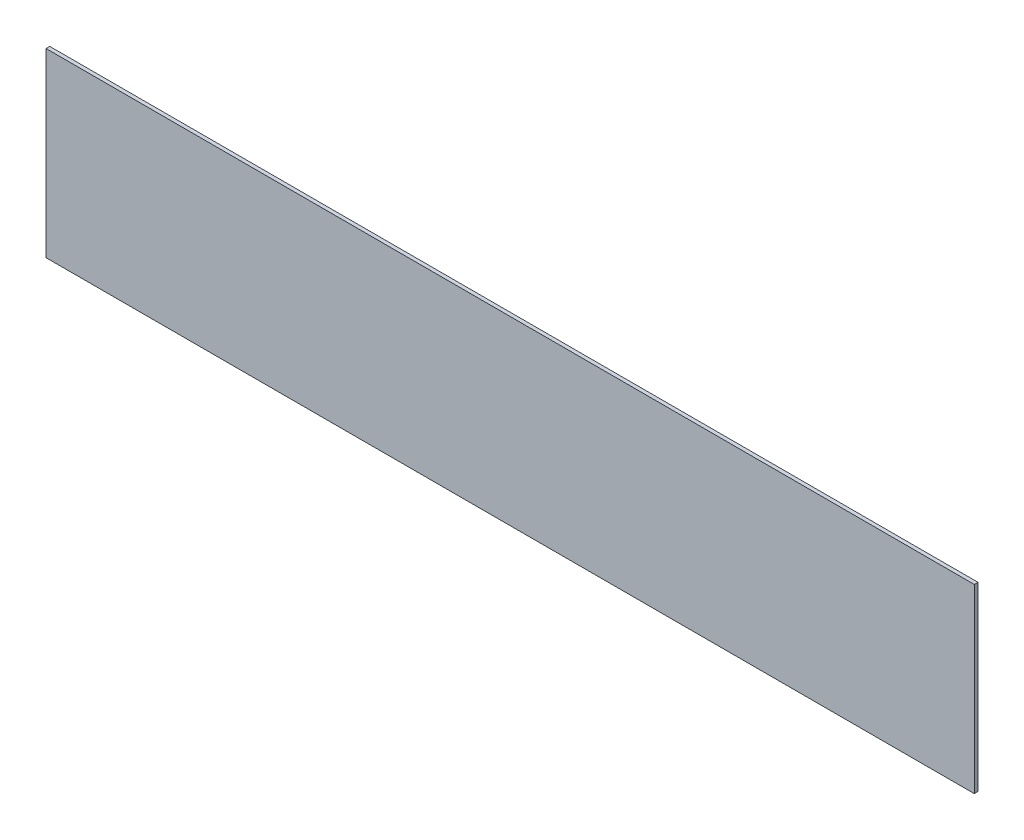
SolidWorks part; units mm, degrees
ref_plane "Front Plane" through (0, 0, 0) normal (0, 0, 1) x (1, 0, 0)
ref_plane "Top Plane" through (0, 0, 0) normal (0, 1, 0) x (1, 0, 0)
ref_plane "Right Plane" through (0, 0, 0) normal (1, 0, 0) x (0, 0, -1)
sketch "Sketch1" plane through (0, 0, 0) normal (0, 0, 1) x (1, 0, 0)
  line L0 (0, 0) -> (0, 49)
  line L1 (0, 49) -> (251.04, 49)
  line L2 (251.04, 49) -> (251.04, 0)
  line L3 (251.04, 0) -> (0, 0)
  dimension "D1" = 49
  dimension "D2" = 251.04
extrude "Boss-Extrude1" add sketch "Sketch1" along normal blind 1
